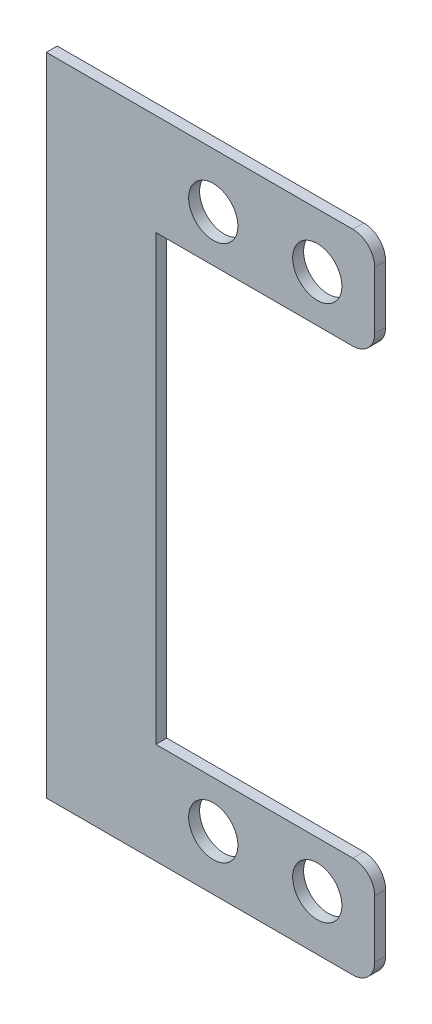
SolidWorks part; units mm, degrees
ref_plane "Front Plane" through (0, 0, 0) normal (0, 0, 1) x (1, 0, 0)
ref_plane "Top Plane" through (0, 0, 0) normal (0, 1, 0) x (1, 0, 0)
ref_plane "Right Plane" through (0, 0, 0) normal (1, 0, 0) x (0, 0, -1)
sketch "Sketch1" plane through (0, 0, 0) normal (0, 0, 1) x (1, 0, 0)
  line L0 (20, 42.5) -> (20, 47.75)
  line L1 (0, 0) -> (18, 0)
  line L2 (0, 0) -> (0, 40.5)
  line L3 (0, 40.5) -> (18, 40.5)
  line L4 (-10, -9.25) -> (-10, 49.75)
  line L7 (20, -7.25) -> (20, -2)
  line L12 (18, 49.75) -> (-10, 49.75)
  line L13 (18, -9.25) -> (-10, -9.25)
  circle A0 centre (5.25, 44.75) radius 2.25
  circle A1 centre (14.75, 44.75) radius 2.25
  circle A2 centre (14.75, -4.25) radius 2.25
  circle A3 centre (5.25, -4.25) radius 2.25
  arc A12 (18, 40.5) -> (20, 42.5) centre (18, 42.5) ccw
  arc A13 (20, 47.75) -> (18, 49.75) centre (18, 47.75) ccw
  arc A14 (18, 0) -> (20, -2) centre (18, -2) cw
  arc A15 (20, -7.25) -> (18, -9.25) centre (18, -7.25) cw
  dimension "D6" = 4.5
  dimension "D7" = 4.5
  dimension "D8" = 4.5
  dimension "D9" = 4.5
  dimension "D25" = 2
  dimension "D1" = 40.5
  dimension "D2" = 20
  dimension "D3" = 20
  dimension "D4" = 9.5
  dimension "D5" = 9.5
  dimension "D10" = 4.25
  dimension "D11" = 4.25
  dimension "D12" = 5.25
  dimension "D13" = 5.25
  dimension "D14" = 5.25
  dimension "D15" = 5.25
  dimension "D16" = 10
  dimension "D17" = 9.25
  dimension "D18" = 9.25
extrude "Boss-Extrude1" add sketch "Sketch1" along normal blind 1
